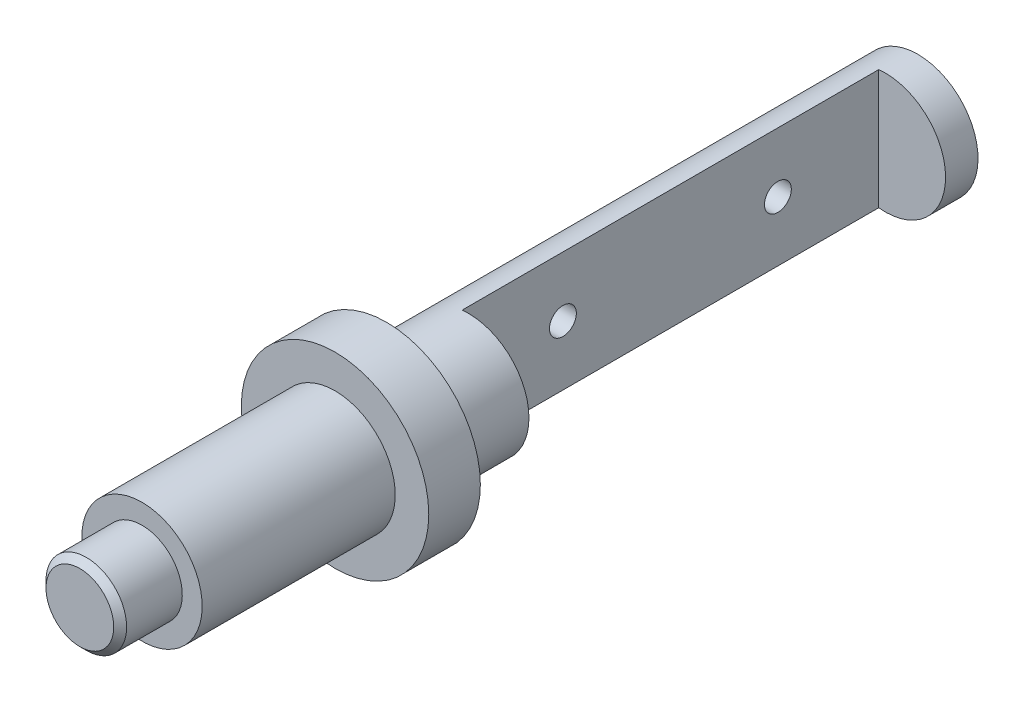
SolidWorks part; units mm, degrees
ref_plane "Front Plane" through (0, 0, 0) normal (0, 0, 1) x (1, 0, 0)
ref_plane "Top Plane" through (0, 0, 0) normal (0, 1, 0) x (1, 0, 0)
ref_plane "Right Plane" through (0, 0, 0) normal (1, 0, 0) x (0, 0, -1)
sketch "Sketch1" plane through (0, 0, 0) normal (1, 0, 0) x (0, 0, -1)
  line L0 (0, 0) -> (0, 18.75)
  line L1 (0, 18.75) -> (28.9, 18.75)
  line L2 (28.9, 18.75) -> (28.9, 28)
  line L3 (28.9, 28) -> (118.7, 28)
  line L4 (118.7, 28) -> (118.7, 43.6)
  line L5 (118.7, 43.6) -> (142.7, 43.6)
  line L6 (142.7, 43.6) -> (142.7, 28)
  line L7 (142.7, 28) -> (389.8, 28)
  line L8 (389.8, 28) -> (389.8, 0)
  line L9 (389.8, 0) -> (0, 0)
  point P3 (129.7723, 28)
  point P13 (389.8, 14)
  dimension "D1" = 28
  dimension "D2" = 43.6
  dimension "D3" = 18.75
  dimension "D4" = 28
  dimension "D5" = 28.9
  dimension "D6" = 89.8
  dimension "D7" = 24
  dimension "D8" = 247.1
revolve "Revolve1" add sketch "Sketch1" angle 360 about L9
sketch "Sketch2" plane through (0, 0, 0) normal (0, 1, 0) x (1, 0, 0)
  line L0 (28, 142.7) -> (28, 389.8) construction
  line L1 (28, 180.9) -> (-3.1, 180.9)
  line L2 (28, 180.9) -> (28, 374.7)
  line L3 (28, 374.7) -> (-3.1, 374.7)
  line L4 (-3.1, 180.9) -> (-3.1, 374.7)
  line L5 (28, 389.8) -> (-28, 389.8) construction
  dimension "D1" = 193.8
  dimension "D2" = 31.1
  dimension "D3" = 15.1
extrude "Cut-Extrude1" cut sketch "Sketch2" against normal through all both and the other way through all
sketch "Sketch3" plane through (-3.1, 0, 0) normal (1, 0, 0) x (0, 0, -1)
  line L0 (180.9, -28) -> (180.9, 28) construction
  circle A0 centre (227.8, 0) radius 6.25
  circle A1 centre (327.8, 0) radius 6.25
  point P4 (0, 0)
  dimension "D1" = 100
  dimension "D3" = 12.5
  dimension "D4" = 12.5
  dimension "D2" = 46.9
extrude "Cut-Extrude2" cut sketch "Sketch3" against normal through all
chamfer "Chamfer1" distance 3 angle 45 1 edges at (0, 18.75, 0)
